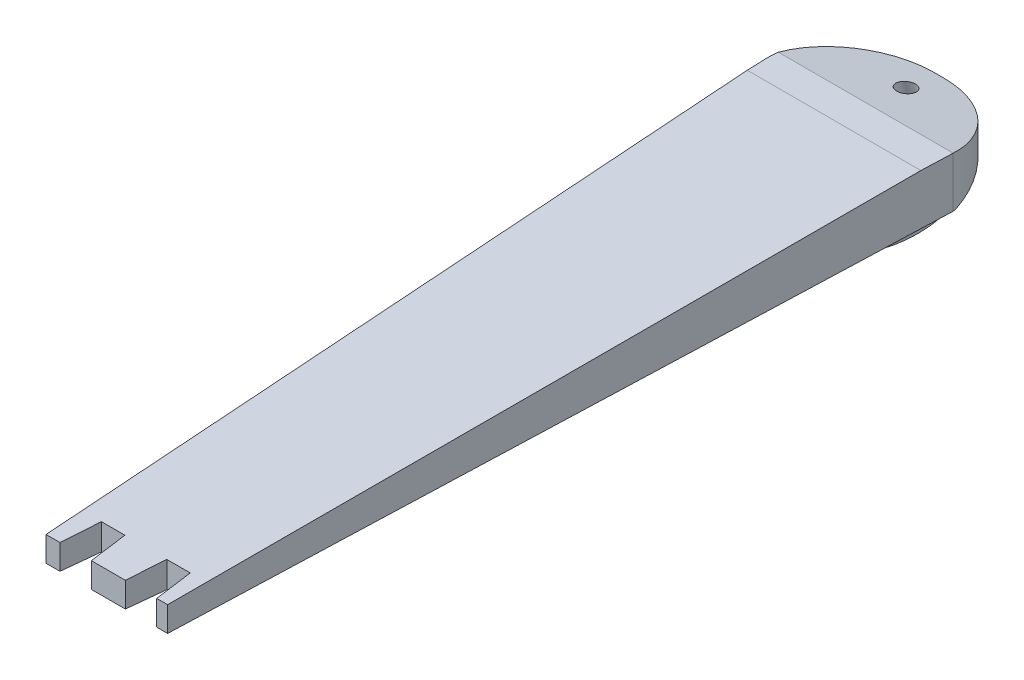
SolidWorks part; units mm, degrees
ref_plane "Ebene vorne" through (0, 0, 0) normal (0, 0, 1) x (1, 0, 0)
ref_plane "Ebene oben" through (0, 0, 0) normal (0, 1, 0) x (1, 0, 0)
ref_plane "Ebene rechts" through (0, 0, 0) normal (1, 0, 0) x (0, 0, -1)
sketch "Skizze1" plane through (0, 0, 0) normal (0, 1, 0) x (1, 0, 0)
  line L0 (9.5572, 20.3887) -> (6.3217, -70)
  line L1 (-1.3628, 29.1262) -> (-0.3628, 29.1262)
  line L3 (-8.1726, -70) -> (-6.5079, -70)
  line L5 (-7.0335, 23.4152) -> (7.8875, -26.2583) construction
  line L6 (-9.7157, -26.8895) -> (7.9093, 21.89) construction
  line L7 (-11.3628, 19.1262) -> (-8.1726, -70)
  line L8 (-8.1726, -70) -> (-6.5079, -70)
  line L9 (-6.5079, -70) -> (-6.0384, -65.5334)
  line L10 (-6.0384, -65.5334) -> (-3.2384, -65.5334)
  line L11 (-3.2384, -65.5334) -> (-2.7689, -70)
  line L18 (-2.7689, -70) -> (1.2828, -70)
  line L19 (1.2828, -70) -> (1.7523, -65.5334)
  line L20 (1.7523, -65.5334) -> (4.5523, -65.5334)
  line L21 (4.5523, -65.5334) -> (5.0217, -70)
  line L22 (5.0217, -70) -> (6.3217, -70)
  arc A0 (-0.3628, 29.1262) -> (9.5572, 20.3887) centre (-0.3628, 19.1262) cw
  arc A1 (-11.3628, 19.1262) -> (-1.3628, 29.1262) centre (-1.3628, 19.1262) cw
  point P0 (0, 0)
  dimension "D1" = 10
  dimension "D2" = 87.95
  dimension "D3" = 87.95
  dimension "D4" = 2.8
  dimension "D5" = 1
  dimension "D6" = 96
  dimension "D7" = 96
  dimension "D8" = 0
  dimension "D9" = 4.4666
  dimension "D10" = 1.3
  dimension "D12" = 96
  dimension "D13" = 96
  dimension "D14" = 2.8
extrude "Aufsatz-Linear austragen1" add sketch "Skizze1" along normal blind 6
sketch "Skizze3" plane through (0, 0, 0) normal (1, 0, 0) x (0, 0, -1)
  line L0 (29.1262, 6) -> (20.3887, 6) construction
  line L1 (16.6737, 6) -> (-70, 6)
  line L9 (20.3887, 6) -> (-70, 6) construction
  line L10 (-70, 6) -> (-70, 2.9733)
  line L11 (-70, 6) -> (-70, 0) construction
  line L12 (-70, 2.9733) -> (16.6737, 6)
  dimension "D1" = 2
extrude "Schnitt-Linear austragen1" cut sketch "Skizze3" against normal through all and the other way through all contours L1 L10 L12
sketch "Skizze4" plane through (0, 0, 0) normal (1, 0, 0) x (0, 0, -1)
  line L4 (20.3887, 6) -> (29.1262, 4.4593)
  line L7 (29.1262, 6) -> (29.1262, 0) construction
  line L10 (20.3887, 6) -> (29.1262, 6)
  line L11 (29.1262, 6) -> (29.1262, 4.4593)
  dimension "D1" = 10
extrude "Schnitt-Linear austragen2" cut sketch "Skizze4" against normal through all and the other way through all
sketch "Skizze5" plane through (0, 0, 0) normal (0, -1, 0) x (1, 0, 0)
  line L1 (-1.3628, -29.1262) -> (-0.3628, -29.1262) construction
  line L2 (-0.8628, -19.1262) -> (-7.9339, -12.0552) construction
  line L7 (-7.9339, -12.0552) -> (-0.8628, -19.1262) construction
  line L8 (-0.8628, -19.1262) -> (6.2082, -12.0552) construction
  line L9 (-7.9339, -12.0552) -> (-7.9339, -3.3714)
  line L10 (-7.9339, -3.3714) -> (6.2082, -3.3714)
  line L11 (6.2082, -3.3714) -> (6.2082, -12.0552)
  arc A2 (-7.9339, -12.0552) -> (6.2082, -12.0552) centre (-0.8628, -19.1262) ccw
  dimension "D1" = 10
  dimension "D2" = 20
extrude "Aufsatz-Linear austragen2" add sketch "Skizze5" along normal blind 4
sketch "Skizze6" plane through (0, 0, 0) normal (1, 0, 0) x (0, 0, -1)
  line L19 (12.0668, -1.9925) -> (29.1262, 1.946)
  line L20 (29.1262, -4) -> (29.1262, 0) construction
  line L21 (29.1262, 1.946) -> (29.1262, -4)
  line L22 (29.1262, -4) -> (3.3714, -4)
  line L23 (12.0668, -1.9925) -> (3.3714, -2)
  line L24 (3.3714, -4) -> (3.3714, 0) construction
  line L25 (3.3714, -2) -> (3.3714, -4)
  dimension "D1" = 13
extrude "Schnitt-Linear austragen3" cut sketch "Skizze6" against normal through all and the other way through all
sketch "Skizze7" plane through (0, -4.5366, -1.0473) normal (0, -0.9744, -0.225) x (1, 0, 0)
  line L3 (-7.9455, -11.3093) -> (6.2199, -11.3093) construction
  line L4 (-0.8628, -11.3093) -> (-0.8628, -24.5948) construction
  circle A7 centre (-0.8628, -14.0093) radius 1.05
  circle A8 centre (-0.8628, -17.9093) radius 1.05
  circle A9 centre (-0.8628, -21.8093) radius 1.05
  circle A10 centre (-0.8628, -25.7093) radius 1.05
  point P10 (0, 0)
  point P14 (0, 0)
  dimension "D1" = 2.1
  dimension "D2" = 2.7
  dimension "D3" = 4
extrude "Schnitt-Linear austragen4" cut sketch "Skizze7" against normal blind 5
